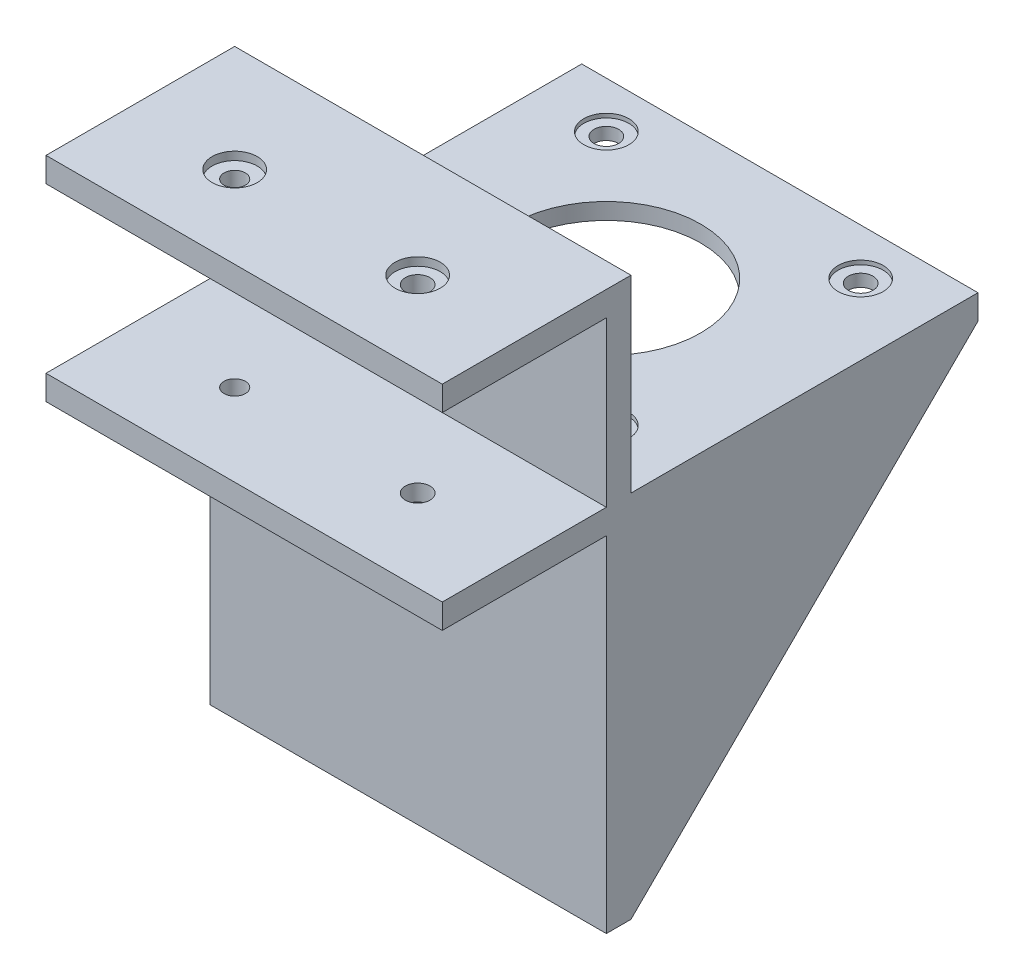
SolidWorks part; units mm, degrees
ref_plane "Front Plane" through (0, 0, 0) normal (0, 0, 1) x (1, 0, 0)
ref_plane "Top Plane" through (0, 0, 0) normal (0, 1, 0) x (1, 0, 0)
ref_plane "Right Plane" through (0, 0, 0) normal (1, 0, 0) x (0, 0, -1)
sketch "Sketch1" plane through (0, 0, 0) normal (0, 1, 0) x (1, 0, 0)
  line L5 (0, 0) -> (42.3, 0)
  line L6 (0, 0) -> (0, 42.3)
  line L7 (0, 42.3) -> (42.3, 42.3)
  line L8 (42.3, 0) -> (42.3, 42.3)
  circle A0 centre (21.15, 21.15) radius 11.5
  dimension "D1" = 42.3
  dimension "D2" = 42.3
extrude "Boss-Extrude2" add sketch "Sketch1" along normal blind 3
sketch "Sketch2" plane through (0, 3, 0) normal (0, 1, 0) x (1, 0, 0)
  circle A0 centre (5.65, 5.65) radius 1.5
  circle A1 centre (5.65, 36.65) radius 1.5
  circle A2 centre (36.65, 36.65) radius 1.5
  circle A3 centre (36.65, 5.65) radius 1.5
extrude "Cut-Extrude1" cut sketch "Sketch2" against normal blind 3
sketch "Sketch3" plane through (0, 0, 0) normal (0, 1, 0) x (1, 0, 0)
  line L1 (0, 0) -> (-3, 0)
  line L2 (0, 0) -> (0, 42.3)
  line L3 (0, 42.3) -> (-3, 42.3)
  line L4 (-3, 0) -> (-3, 42.3)
  dimension "D1" = 3
  dimension "D2" = 42.3
extrude "Boss-Extrude3" add sketch "Sketch3" along normal blind 3 and the other way blind 42
sketch "Sketch5" plane through (0, 0, 0) normal (0, 0, 1) x (1, 0, 0)
  line L1 (-3, 3) -> (42.3, 3)
  line L2 (-3, 3) -> (-3, -42)
  line L3 (-3, -42) -> (42.3, -42)
  line L4 (42.3, 3) -> (42.3, -42)
  dimension "D1" = 45
  dimension "D2" = 45.3
extrude "Boss-Extrude4" add sketch "Sketch5" along normal blind 3
sketch "Sketch6" plane through (0, 0, 0) normal (1, 0, 0) x (0, 0, -1)
  line L0 (0, -42) -> (42.3, -42) construction
  line L1 (0, -42) -> (42.3, 0)
  point P0 (0, -42)
  point P1 (42.3, 0)
extrude "Cut-Extrude3" cut sketch "Sketch6" against normal blind 3 and the other way through all flip side to cut
sketch "Sketch8" plane through (42.3, 0, 0) normal (1, 0, 0) x (0, 0, -1)
  line L1 (-3, 3) -> (42.3, 3)
  line L2 (-3, 3) -> (-3, -42)
  line L3 (-3, -42) -> (42.3, -42)
  line L4 (42.3, 3) -> (42.3, -42)
  dimension "D1" = 45
extrude "Boss-Extrude5" add sketch "Sketch8" along normal blind 3
sketch "Sketch12" plane through (0, 3, 0) normal (0, 1, 0) x (1, 0, 0)
  line L0 (-3, 42.3) -> (-3, -3) construction
  line L1 (45.3, -3) -> (-3, -3)
  line L2 (45.3, -3) -> (45.3, 0)
  line L3 (45.3, 0) -> (-3, 0)
  line L4 (-3, -3) -> (-3, 0)
  point P0 (45.3, -3)
extrude "Boss-Extrude6" add sketch "Sketch12" along normal blind 23
sketch "Sketch14" plane through (0, 0, 3) normal (0, 0, 1) x (1, 0, 0)
  line L0 (45.3, 26) -> (45.3, -42) construction
  line L1 (-3, 26) -> (45.3, 26)
  line L2 (-3, 26) -> (-3, 23)
  line L3 (-3, 23) -> (45.3, 23)
  line L4 (45.3, 26) -> (45.3, 23)
  dimension "D1" = 3
extrude "Boss-Extrude7" add sketch "Sketch14" along normal blind 20
sketch "Sketch17" plane through (0, 3, 0) normal (0, 1, 0) x (1, 0, 0)
  circle A0 centre (36.65, 36.65) radius 2.75
  circle A1 centre (36.65, 5.65) radius 2.75
  circle A2 centre (5.65, 36.65) radius 2.75
  circle A3 centre (5.65, 5.65) radius 2.75
  point P0 (36.65, 5.65)
  point P1 (36.65, 36.65)
  point P2 (5.65, 36.65)
  point P4 (5.65, 5.65)
extrude "Cut-Extrude5" cut sketch "Sketch17" against normal blind 0.5
sketch "Sketch18" plane through (42.3, 0, 0) normal (-1, 0, 0) x (0, 0, 1)
  line L0 (-42.3, 0) -> (0, -42)
  point P0 (-42.3, 0)
  point P1 (0, -42)
extrude "Cut-Extrude6" cut sketch "Sketch18" against normal blind 3 and the other way through all flip side to cut
sketch "Sketch19" plane through (0, 0, 3) normal (0, 0, 1) x (1, 0, 0)
  line L0 (-3, 23) -> (-3, -42) construction
  line L1 (45.3, 23) -> (45.3, -42) construction
  line L2 (-3, 3) -> (45.3, 3)
  line L3 (-3, 3) -> (-3, 0)
  line L4 (-3, 0) -> (45.3, 0)
  line L5 (45.3, 3) -> (45.3, 0)
  point P0 (-3, 3)
extrude "Boss-Extrude8" add sketch "Sketch19" along normal blind 20
sketch "Sketch21" plane through (0, 0, 0) normal (0, 0, -1) x (-1, 0, 0)
  line L1 (-45.3, 26) -> (-45.3, 3) construction
  circle A0 centre (-32.3014, 13) radius 1.5
  circle A1 centre (-10, 13) radius 1.5
  point P0 (-32.3014, 13)
  point P1 (-32.3014, 13)
  point P2 (-10, 13)
  point P3 (-10, 13)
  point P4 (-32.3014, 13)
  point P5 (-10, 13)
  point P6 (38.6208, -6.6746)
  point P7 (-10, 13)
  point P8 (-32.3014, 13)
  point P9 (-45.3, 19.4671)
extrude "Cut-Extrude7" cut sketch "Sketch21" against normal blind 20
sketch "Sketch23" plane through (0, 0, 0) normal (0, 0, -1) x (-1, 0, 0)
  circle A0 centre (-10, 13) radius 2.75
  point P0 (-10, 13)
extrude "Cut-Extrude9" cut sketch "Sketch23" against normal blind 1
sketch "Sketch26" plane through (0, 0, 0) normal (0, 0, -1) x (-1, 0, 0)
  circle A2 centre (-32.3, 13) radius 2.75
  point P0 (-32.3, 13)
extrude "Cut-Extrude10" cut sketch "Sketch26" against normal blind 1
sketch "Sketch27" plane through (0, 26, 0) normal (0, 1, 0) x (1, 0, 0)
  circle A0 centre (10, -13) radius 1.3
  circle A1 centre (32.3, -13) radius 1.5
  point P0 (10, -13)
extrude "Cut-Extrude11" cut sketch "Sketch27" against normal blind 41
sketch "Sketch30" plane through (0, 26, 0) normal (0, 1, 0) x (1, 0, 0)
  circle A0 centre (10, -13) radius 2.75
extrude "Cut-Extrude12" cut sketch "Sketch30" against normal blind 1
sketch "Sketch31" plane through (0, 26, 0) normal (0, 1, 0) x (1, 0, 0)
  circle A0 centre (32.3, -13) radius 2.75
extrude "Cut-Extrude13" cut sketch "Sketch31" against normal blind 1
sketch "Sketch32" plane through (0, 0, 0) normal (0, -1, 0) x (1, 0, 0)
  circle A0 centre (32.3, 13) radius 2.75
extrude "Cut-Extrude14" cut sketch "Sketch32" against normal blind 1
sketch "Sketch33" plane through (0, 0, 0) normal (0, -1, 0) x (1, 0, 0)
  circle A0 centre (10, 13) radius 2.75
extrude "Cut-Extrude15" cut sketch "Sketch33" against normal blind 1
sketch "Sketch37" plane through (0, 0, 23) normal (0, 0, 1) x (1, 0, 0)
  point P0 (45.2917, 25.9709)
sketch "Sketch38" plane through (0, 0, 0) normal (0, -1, 0) x (-1, 0, 0)
  line L1 (-42.3, 42.3) -> (0, 42.3)
  line L2 (-42.3, 42.3) -> (-42.3, 0)
  line L3 (-42.3, 0) -> (0, 0)
  line L4 (0, 42.3) -> (0, 0)
extrude "Cut-Extrude16" cut sketch "Sketch38" against normal blind 1
